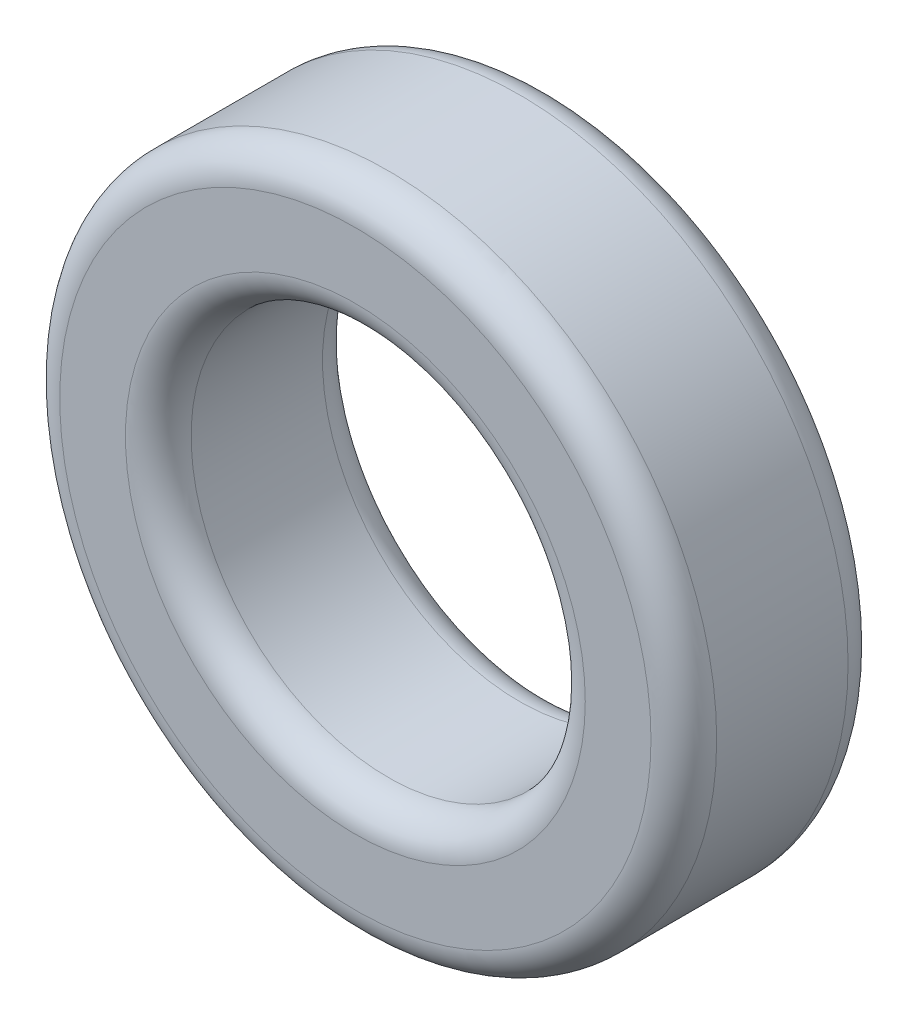
SolidWorks part; units mm, degrees
ref_plane "前视基准面" through (0, 0, 0) normal (0, 0, 1) x (1, 0, 0)
ref_plane "上视基准面" through (0, 0, 0) normal (0, 1, 0) x (1, 0, 0)
ref_plane "右视基准面" through (0, 0, 0) normal (1, 0, 0) x (0, 0, -1)
other "Configuration Table"
sketch "草图1" plane through (0, 0, 0) normal (0, 0, 1) x (1, 0, 0)
  circle A0 centre (0, 0) radius 3
  circle A1 centre (0, 0) radius 5
  dimension "D1" = 6
  dimension "D2" = 10
extrude "凸台-拉伸1" add sketch "草图1" along normal blind 3
fillet "圆角1" radius 0.5 4 edges at (3, 0, 0) (3, 0, 3) (5, 0, 0) (5, 0, 3)
